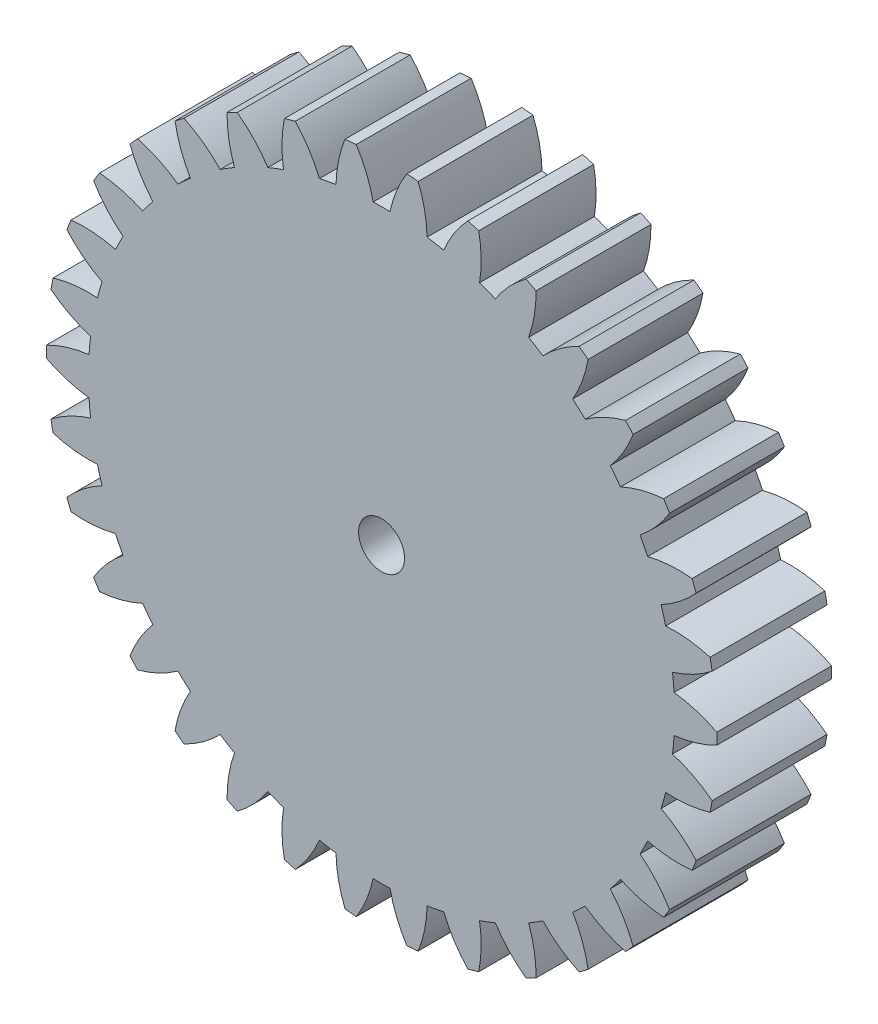
SolidWorks part; units mm, degrees
ref_plane "Front Plane" through (0, 0, 0) normal (0, 0, 1) x (1, 0, 0)
ref_plane "Top Plane" through (0, 0, 0) normal (0, 1, 0) x (1, 0, 0)
ref_plane "Right Plane" through (0, 0, 0) normal (1, 0, 0) x (0, 0, -1)
sketch "Sketch1" plane through (0, 0, 0) normal (0, 0, 1) x (1, 0, 0)
  arc A0 (-14.5894, -0.2465) -> (-12.7303, -0.8118) centre (-12.0814, 4.6622) ccw
  arc A1 (-12.7303, -0.8118) -> (-12.6628, -1.5413) centre (0, 0) ccw
  arc A2 (-12.6628, -1.5413) -> (-14.3863, -2.4385) centre (-11.019, -6.8028) ccw
  arc A3 (-14.3863, -2.4385) -> (-14.2957, -2.9231) centre (0, 0) ccw
  arc A4 (-14.2957, -2.9231) -> (-12.3644, -3.1371) centre (-12.7324, 2.3629) ccw
  arc A5 (-12.3644, -3.1371) -> (-12.1639, -3.8418) centre (0, 0) ccw
  arc A6 (-12.1639, -3.8418) -> (-13.6933, -5.0404) centre (-9.5814, -8.7117) ccw
  arc A7 (-13.6933, -5.0404) -> (-13.5152, -5.5002) centre (0, 0) ccw
  arc A8 (-13.5152, -5.5002) -> (-11.5775, -5.3557) centre (-12.9498, -0.0169) ccw
  arc A9 (-11.5775, -5.3557) -> (-11.2509, -6.0115) centre (0, 0) ccw
  arc A10 (-11.2509, -6.0115) -> (-12.5339, -7.4708) centre (-7.8174, -10.3239) ccw
  arc A11 (-12.5339, -7.4708) -> (-12.2744, -7.8899) centre (0, 0) ccw
  arc A12 (-12.2744, -7.8899) -> (-10.3962, -7.3918) centre (-12.7262, -2.3961) ccw
  arc A13 (-10.3962, -7.3918) -> (-9.9547, -7.9765) centre (0, 0) ccw
  arc A14 (-9.9547, -7.9765) -> (-10.9478, -9.6467) centre (-5.7873, -11.5846) ccw
  arc A15 (-10.9478, -9.6467) -> (-10.6156, -10.011) centre (0, 0) ccw
  arc A16 (-10.6156, -10.011) -> (-8.861, -9.1763) centre (-12.0692, -4.6937) ccw
  arc A17 (-8.861, -9.1763) -> (-8.3196, -9.6698) centre (0, 0) ccw
  arc A18 (-8.3196, -9.6698) -> (-8.9888, -11.494) centre (-3.5601, -12.4508) ccw
  arc A19 (-8.9888, -11.494) -> (-8.5954, -11.7911) centre (0, 0) ccw
  arc A20 (-8.5954, -11.7911) -> (-7.0239, -10.6482) centre (-11.0012, -6.8315) ccw
  arc A21 (-7.0239, -10.6482) -> (-6.4011, -11.0339) centre (0, 0) ccw
  arc A22 (-6.4011, -11.0339) -> (-6.7237, -12.95) centre (-1.2117, -12.893) ccw
  arc A23 (-6.7237, -12.95) -> (-6.2824, -13.1698) centre (0, 0) ccw
  arc A24 (-6.2824, -13.1698) -> (-4.9477, -11.7576) centre (-9.5586, -8.7367) ccw
  arc A25 (-4.9477, -11.7576) -> (-4.2646, -12.0222) centre (0, 0) ccw
  arc A26 (-4.2646, -12.0222) -> (-4.2297, -13.965) centre (1.178, -12.8961) ccw
  arc A27 (-4.2297, -13.965) -> (-3.7555, -14.0999) centre (0, 0) ccw
  arc A28 (-3.7555, -14.0999) -> (-2.703, -12.4665) centre (-7.7905, -10.3443) ccw
  arc A29 (-2.703, -12.4665) -> (-1.9829, -12.6011) centre (0, 0) ccw
  arc A30 (-1.9829, -12.6011) -> (-1.5916, -14.5044) centre (3.5276, -12.46) ccw
  arc A31 (-1.5916, -14.5044) -> (-1.1007, -14.5499) centre (0, 0) ccw
  arc A32 (-1.1007, -14.5499) -> (-0.3663, -12.7509) centre (-5.7571, -11.5997) ccw
  arc A33 (-0.3663, -12.7509) -> (0.3663, -12.7509) centre (0, 0) ccw
  arc A34 (0.3663, -12.7509) -> (1.1007, -14.5499) centre (5.7571, -11.5997) ccw
  arc A35 (1.1007, -14.5499) -> (1.5916, -14.5044) centre (0, 0) ccw
  arc A36 (1.5916, -14.5044) -> (1.9829, -12.6011) centre (-3.5276, -12.46) ccw
  arc A37 (1.9829, -12.6011) -> (2.703, -12.4665) centre (0, 0) ccw
  arc A38 (2.703, -12.4665) -> (3.7555, -14.0999) centre (7.7905, -10.3443) ccw
  arc A39 (3.7555, -14.0999) -> (4.2297, -13.965) centre (0, 0) ccw
  arc A40 (4.2297, -13.965) -> (4.2646, -12.0222) centre (-1.178, -12.8961) ccw
  arc A41 (4.2646, -12.0222) -> (4.9477, -11.7576) centre (0, 0) ccw
  arc A42 (4.9477, -11.7576) -> (6.2824, -13.1698) centre (9.5586, -8.7367) ccw
  arc A43 (6.2824, -13.1698) -> (6.7237, -12.95) centre (0, 0) ccw
  arc A44 (6.7237, -12.95) -> (6.4011, -11.0339) centre (1.2117, -12.893) ccw
  arc A45 (6.4011, -11.0339) -> (7.0239, -10.6482) centre (0, 0) ccw
  arc A46 (7.0239, -10.6482) -> (8.5954, -11.7911) centre (11.0012, -6.8315) ccw
  arc A47 (8.5954, -11.7911) -> (8.9888, -11.494) centre (0, 0) ccw
  arc A48 (8.9888, -11.494) -> (8.3196, -9.6698) centre (3.5601, -12.4508) ccw
  arc A49 (8.3196, -9.6698) -> (8.861, -9.1763) centre (0, 0) ccw
  arc A50 (8.861, -9.1763) -> (10.6156, -10.011) centre (12.0692, -4.6937) ccw
  arc A51 (10.6156, -10.011) -> (10.9478, -9.6467) centre (0, 0) ccw
  arc A52 (10.9478, -9.6467) -> (9.9547, -7.9765) centre (5.7873, -11.5846) ccw
  arc A53 (9.9547, -7.9765) -> (10.3962, -7.3918) centre (0, 0) ccw
  arc A54 (10.3962, -7.3918) -> (12.2744, -7.8899) centre (12.7262, -2.3961) ccw
  arc A55 (12.2744, -7.8899) -> (12.5339, -7.4708) centre (0, 0) ccw
  arc A56 (12.5339, -7.4708) -> (11.2509, -6.0115) centre (7.8174, -10.3239) ccw
  arc A57 (11.2509, -6.0115) -> (11.5775, -5.3557) centre (0, 0) ccw
  arc A58 (11.5775, -5.3557) -> (13.5152, -5.5002) centre (12.9498, -0.0169) ccw
  arc A59 (13.5152, -5.5002) -> (13.6933, -5.0404) centre (0, 0) ccw
  arc A60 (13.6933, -5.0404) -> (12.1639, -3.8418) centre (9.5814, -8.7117) ccw
  arc A61 (12.1639, -3.8418) -> (12.3644, -3.1371) centre (0, 0) ccw
  arc A62 (12.3644, -3.1371) -> (14.2957, -2.9231) centre (12.7324, 2.3629) ccw
  arc A63 (14.2957, -2.9231) -> (14.3863, -2.4385) centre (0, 0) ccw
  arc A64 (14.3863, -2.4385) -> (12.6628, -1.5413) centre (11.019, -6.8028) ccw
  arc A65 (12.6628, -1.5413) -> (12.7303, -0.8118) centre (0, 0) ccw
  arc A66 (12.7303, -0.8118) -> (14.5894, -0.2465) centre (12.0814, 4.6622) ccw
  arc A67 (14.5894, -0.2465) -> (14.5894, 0.2465) centre (0, 0) ccw
  arc A68 (14.5894, 0.2465) -> (12.7303, 0.8118) centre (12.0814, -4.6622) ccw
  arc A69 (12.7303, 0.8118) -> (12.6628, 1.5413) centre (0, 0) ccw
  arc A70 (12.6628, 1.5413) -> (14.3863, 2.4385) centre (11.019, 6.8028) ccw
  arc A71 (14.3863, 2.4385) -> (14.2957, 2.9231) centre (0, 0) ccw
  arc A72 (14.2957, 2.9231) -> (12.3644, 3.1371) centre (12.7324, -2.3629) ccw
  arc A73 (12.3644, 3.1371) -> (12.1639, 3.8418) centre (0, 0) ccw
  arc A74 (12.1639, 3.8418) -> (13.6933, 5.0404) centre (9.5814, 8.7117) ccw
  arc A75 (13.6933, 5.0404) -> (13.5152, 5.5002) centre (0, 0) ccw
  arc A76 (13.5152, 5.5002) -> (11.5775, 5.3557) centre (12.9498, 0.0169) ccw
  arc A77 (11.5775, 5.3557) -> (11.2509, 6.0115) centre (0, 0) ccw
  arc A78 (11.2509, 6.0115) -> (12.5339, 7.4708) centre (7.8174, 10.3239) ccw
  arc A79 (12.5339, 7.4708) -> (12.2744, 7.8899) centre (0, 0) ccw
  arc A80 (12.2744, 7.8899) -> (10.3962, 7.3918) centre (12.7262, 2.3961) ccw
  arc A81 (10.3962, 7.3918) -> (9.9547, 7.9765) centre (0, 0) ccw
  arc A82 (9.9547, 7.9765) -> (10.9478, 9.6467) centre (5.7873, 11.5846) ccw
  arc A83 (10.9478, 9.6467) -> (10.6156, 10.011) centre (0, 0) ccw
  arc A84 (10.6156, 10.011) -> (8.861, 9.1763) centre (12.0692, 4.6937) ccw
  arc A85 (8.861, 9.1763) -> (8.3196, 9.6698) centre (0, 0) ccw
  arc A86 (8.3196, 9.6698) -> (8.9888, 11.494) centre (3.5601, 12.4508) ccw
  arc A87 (8.9888, 11.494) -> (8.5954, 11.7911) centre (0, 0) ccw
  arc A88 (8.5954, 11.7911) -> (7.0239, 10.6482) centre (11.0012, 6.8315) ccw
  arc A89 (7.0239, 10.6482) -> (6.4011, 11.0339) centre (0, 0) ccw
  arc A90 (6.4011, 11.0339) -> (6.7237, 12.95) centre (1.2117, 12.893) ccw
  arc A91 (6.7237, 12.95) -> (6.2824, 13.1698) centre (0, 0) ccw
  arc A92 (6.2824, 13.1698) -> (4.9477, 11.7576) centre (9.5586, 8.7367) ccw
  arc A93 (4.9477, 11.7576) -> (4.2646, 12.0222) centre (0, 0) ccw
  arc A94 (4.2646, 12.0222) -> (4.2297, 13.965) centre (-1.178, 12.8961) ccw
  arc A95 (4.2297, 13.965) -> (3.7555, 14.0999) centre (0, 0) ccw
  arc A96 (3.7555, 14.0999) -> (2.703, 12.4665) centre (7.7905, 10.3443) ccw
  arc A97 (2.703, 12.4665) -> (1.9829, 12.6011) centre (0, 0) ccw
  arc A98 (1.9829, 12.6011) -> (1.5916, 14.5044) centre (-3.5276, 12.46) ccw
  arc A99 (1.5916, 14.5044) -> (1.1007, 14.5499) centre (0, 0) ccw
  arc A100 (1.1007, 14.5499) -> (0.3663, 12.7509) centre (5.7571, 11.5997) ccw
  arc A101 (0.3663, 12.7509) -> (-0.3663, 12.7509) centre (0, 0) ccw
  arc A102 (-0.3663, 12.7509) -> (-1.1007, 14.5499) centre (-5.7571, 11.5997) ccw
  arc A103 (-1.1007, 14.5499) -> (-1.5916, 14.5044) centre (0, 0) ccw
  arc A104 (-1.5916, 14.5044) -> (-1.9829, 12.6011) centre (3.5276, 12.46) ccw
  arc A105 (-1.9829, 12.6011) -> (-2.703, 12.4665) centre (0, 0) ccw
  arc A106 (-2.703, 12.4665) -> (-3.7555, 14.0999) centre (-7.7905, 10.3443) ccw
  arc A107 (-3.7555, 14.0999) -> (-4.2297, 13.965) centre (0, 0) ccw
  arc A108 (-4.2297, 13.965) -> (-4.2646, 12.0222) centre (1.178, 12.8961) ccw
  arc A109 (-4.2646, 12.0222) -> (-4.9477, 11.7576) centre (0, 0) ccw
  arc A110 (-4.9477, 11.7576) -> (-6.2824, 13.1698) centre (-9.5586, 8.7367) ccw
  arc A111 (-6.2824, 13.1698) -> (-6.7237, 12.95) centre (0, 0) ccw
  arc A112 (-6.7237, 12.95) -> (-6.4011, 11.0339) centre (-1.2117, 12.893) ccw
  arc A113 (-6.4011, 11.0339) -> (-7.0239, 10.6482) centre (0, 0) ccw
  arc A114 (-7.0239, 10.6482) -> (-8.5954, 11.7911) centre (-11.0012, 6.8315) ccw
  arc A115 (-8.5954, 11.7911) -> (-8.9888, 11.494) centre (0, 0) ccw
  arc A116 (-8.9888, 11.494) -> (-8.3196, 9.6698) centre (-3.5601, 12.4508) ccw
  arc A117 (-8.3196, 9.6698) -> (-8.861, 9.1763) centre (0, 0) ccw
  arc A118 (-8.861, 9.1763) -> (-10.6156, 10.011) centre (-12.0692, 4.6937) ccw
  arc A119 (-10.6156, 10.011) -> (-10.9478, 9.6467) centre (0, 0) ccw
  arc A120 (-10.9478, 9.6467) -> (-9.9547, 7.9765) centre (-5.7873, 11.5846) ccw
  arc A121 (-9.9547, 7.9765) -> (-10.3962, 7.3918) centre (0, 0) ccw
  arc A122 (-10.3962, 7.3918) -> (-12.2744, 7.8899) centre (-12.7262, 2.3961) ccw
  arc A123 (-12.2744, 7.8899) -> (-12.5339, 7.4708) centre (0, 0) ccw
  arc A124 (-12.5339, 7.4708) -> (-11.2509, 6.0115) centre (-7.8174, 10.3239) ccw
  arc A125 (-11.2509, 6.0115) -> (-11.5775, 5.3557) centre (0, 0) ccw
  arc A126 (-11.5775, 5.3557) -> (-13.5152, 5.5002) centre (-12.9498, 0.0169) ccw
  arc A127 (-13.5152, 5.5002) -> (-13.6933, 5.0404) centre (0, 0) ccw
  arc A128 (-13.6933, 5.0404) -> (-12.1639, 3.8418) centre (-9.5814, 8.7117) ccw
  arc A129 (-12.1639, 3.8418) -> (-12.3644, 3.1371) centre (0, 0) ccw
  arc A130 (-12.3644, 3.1371) -> (-14.2957, 2.9231) centre (-12.7324, -2.3629) ccw
  arc A131 (-14.2957, 2.9231) -> (-14.3863, 2.4385) centre (0, 0) ccw
  arc A132 (-14.3863, 2.4385) -> (-12.6628, 1.5413) centre (-11.019, 6.8028) ccw
  arc A133 (-12.6628, 1.5413) -> (-12.7303, 0.8118) centre (0, 0) ccw
  arc A134 (-12.7303, 0.8118) -> (-14.5894, 0.2465) centre (-12.0814, -4.6622) ccw
  arc A135 (-14.5894, 0.2465) -> (-14.5894, -0.2465) centre (0, 0) ccw
  circle A136 centre (0, 0) radius 2.4
  dimension "D1" = 4.8
extrude "Boss-Extrude1" add sketch "Sketch1" along normal blind 5
sketch "Sketch4" plane through (0, 0, 5) normal (0, 0, 1) x (1, 0, 0)
  circle A0 centre (0, 0) radius 1
  circle A1 centre (0, 0) radius 2.4 construction
  circle A2 centre (0, 0) radius 2.4
  dimension "D1" = 2
extrude "Boss-Extrude2" add sketch "Sketch4" against normal blind 2
